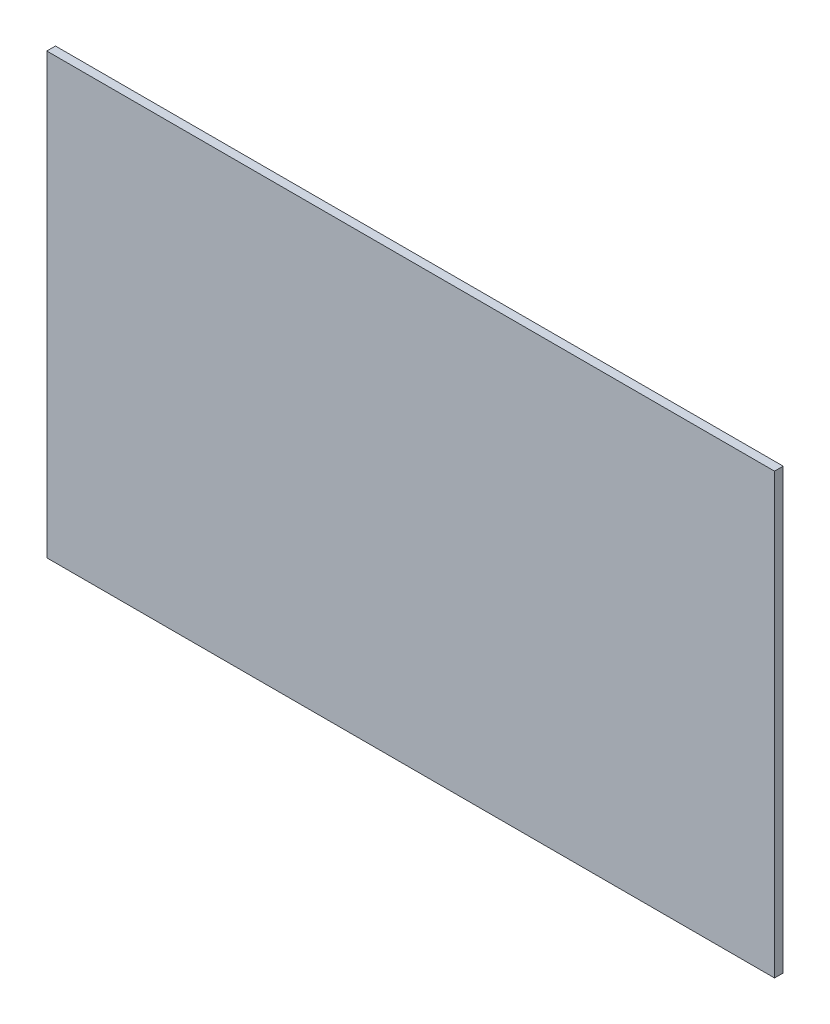
SolidWorks part; units mm, degrees
material "Pine"
ref_plane "Front Plane" through (0, 0, 0) normal (0, 0, 1) x (1, 0, 0)
ref_plane "Top Plane" through (0, 0, 0) normal (0, 1, 0) x (1, 0, 0)
ref_plane "Right Plane" through (0, 0, 0) normal (1, 0, 0) x (0, 0, -1)
sketch "Sketch1" plane through (0, 0, 0) normal (0, 0, 1) x (1, 0, 0)
  line L1 (0, 0) -> (1600.2, 0)
  line L2 (0, 0) -> (0, -965.2)
  line L3 (0, -965.2) -> (1600.2, -965.2)
  line L4 (1600.2, 0) -> (1600.2, -965.2)
  dimension "D1" = 1600.2
  dimension "D2" = 965.2
extrude "Boss-Extrude1" add sketch "Sketch1" along normal blind 19.05
equation "\"TableFrontWidth\"=48"
equation "\"TableSideWidth\"=66"
equation "\"LegWidth\"=3.5"
equation "\"LegHeight\"=30"
equation "\"LegDistToBottomStretcher\"=7"
equation "\"BottomStretcherLength\"=\"TableFrontWidth\""
equation "\"SideStretcherLength\"=\"TableSideWidth\"-3"
equation "\"BottomSupportLength\"=\"TableSideWidth\"-3"
equation "\"BottomPlywoodFrontDim\"=\"TableFrontWidth\"-\"LegWidth\"*2-3"
equation "\"BottomPlywoodSideDim\"=\"BottomSupportLength\""
equation "\"D2@Sketch1\"=\"BottomPlywoodFrontDim\""
equation "\"D1@Sketch1\"=\"BottomPlywoodSideDim\""
equation "\"TotalBottomSupports\"=4"
equation "\"TotalBottomSupportsLessOne\"=\"TotalBottomSupports\"-1"
equation "\"TotalTopSupports\"=5"
equation "\"TotalTopSupportsLessOne\"=\"TotalTopSupports\"-1"
equation "\"TopSupportSpread\"=\"TableFrontWidth\"-1.5"
equation "\"DistBetweenTopSupports\"=\"TopSupportSpread\"/\"TotalTopSupportsLessOne\""
equation "\"BottomSupportSpread\"= \"BottomPlywoodFrontDim\" - 1.5"
equation "\"DistBetweenBottomSupports\"=\"BottomSupportSpread\"/\"TotalBottomSupportsLessOne\""
